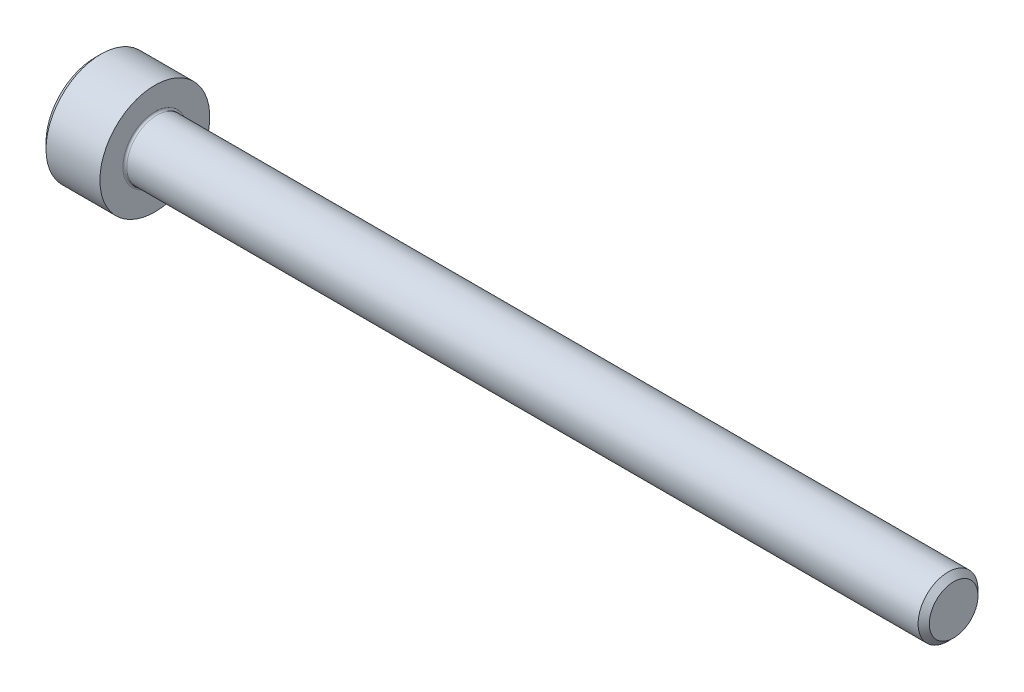
SolidWorks part; units mm, degrees
ref_plane "Plane1" through (0, 0, 0) normal (0, 0, 1) x (1, 0, 0)
ref_plane "Plane2" through (0, 0, 0) normal (0, 1, 0) x (1, 0, 0)
ref_plane "Plane3" through (0, 0, 0) normal (1, 0, 0) x (0, 0, -1)
sketch "BodySke" plane through (0, 0, 0) normal (0, 0, 1) x (1, 0, 0)
  line L0 (0, 0) -> (0, 2.45)
  line L1 (0.3, 2.75) -> (3, 2.75)
  line L2 (3, 2.75) -> (3, 1.5)
  line L3 (3, 1.5) -> (42.7195, 1.5)
  line L4 (43, 1.2195) -> (43, 0)
  line L5 (43, 0) -> (0, 0)
  line L6 (-31.75, 0) -> (127, 0) construction
  line L7 (0, 2.45) -> (0.3, 2.75)
  line L8 (43, 1.2195) -> (42.7195, 1.5)
  line L9 (0, -2.45) -> (0.3, -2.75) construction
  line L10 (43, -1.2195) -> (42.7195, -1.5) construction
  line L11 (3.5, 9.525) -> (3.5, 3.175) construction
  line L12 (25, 9.525) -> (25, 3.175) construction
  line L13 (-7, 9.525) -> (-7, 3.175) construction
  dimension "Diameter" = 3
  dimension "Head_ht" = 3
  dimension "Length" = 40
  dimension "Body_ch_ang" = 45
  dimension "Head_dia" = 5.5
  dimension "Head_ch_ang" = 45
  dimension "Minor_dia" = 2.439
  dimension "Advance" = 0.5
  dimension "Thread_nom" = 18
  dimension "Thread_length" = 50
  dimension "Head_ch_ht" = 0.3
revolve "Base-Revolve" add sketch "BodySke"
cosmetic thread "ThreadCosmetic" [suppressed]
fillet "Fillet1" radius 0.1 1 edges at (3, 0, 1.5)
sketch "Sketch2" plane through (0, 0, 0) normal (0, 0, 1) x (1, 0, 0)
  line L0 (0, 1.28) -> (1.3, 1.28)
  line L1 (1.3, 1.28) -> (2.039, 0)
  line L2 (-31.75, 0) -> (127, 0) construction
  line L3 (2.039, 0) -> (0, 0)
  line L4 (0, 0) -> (0, 1.28)
  line L5 (0, 2.45) -> (0, -2.45) construction
  line L6 (0, 0) -> (47.625, 0) construction
  line L7 (3, -2.75) -> (3, 2.75) construction
  dimension "D1" = 1.28
  dimension "D2" = 60
  dimension "Wall_thickness" = 1.7
revolve "Hex-PreBroach" cut sketch "Sketch2" angle 360 about L6
sketch "Sketch3" plane through (0, 0, 0) normal (-1, 0, 0) x (0, 0.5, 0.866)
  line L0 (0.739, 1.28) -> (-0.739, 1.28)
  line L1 (-0.739, 1.28) -> (-1.478, 0)
  line L2 (0.739, 1.28) -> (1.478, 0)
  line L3 (0.739, -1.28) -> (1.478, 0)
  line L4 (0.739, -1.28) -> (-0.739, -1.28)
  line L5 (-0.739, -1.28) -> (-1.478, 0)
  dimension "D1" = 1.28
  dimension "D2" = 1.28
  dimension "Hex_size" = 2.56
extrude "Hex" cut sketch "Sketch3" against normal blind 1.3
sketch "Sketch4" plane through (0, 0, 0) normal (-1, 0, 0) x (0, 0, 1)
  line L0 (0, 0) -> (1.4605, 0)
  line L1 (0, 0) -> (6.1484, 3.5498) construction
  line L2 (0, 0) -> (0.7302, 1.2648)
  line L3 (1.2009, 0.3267) -> (1.3933, 0.4378)
  line L4 (0.8834, 0.8767) -> (1.0758, 0.9877)
  arc A0 (1.2009, 0.3267) -> (0.8834, 0.8767) centre (0, 0) ccw
  arc A1 (1.4605, 0) -> (1.3933, 0.4378) centre (0, 0) ccw
  arc A2 (0.7302, 1.2648) -> (1.0758, 0.9877) centre (0, 0) cw
  dimension "D1" = 30
  dimension "Spline_n_dim" = 2.4892
  dimension "Spline_m_dim" = 2.921
  dimension "D2" = 60
  dimension "D3" = 0.3175
  dimension "Spline_p_dim" = 0.635
extrude "Spline" [suppressed] cut sketch "Sketch4" against normal blind 1.3
pattern_circular "CirPattern1" [suppressed] count 6 every 60
sketch "Sketch5" plane through (0, 0, 0) normal (0, 0, 1) x (1, 0, 0)
  line L0 (-31.75, 0) -> (127, 0) construction
  line L2 (0, 2.45) -> (0, -2.45) construction
  circle A0 centre (1.2, 0) radius 0.475
  dimension "Drilled_hole_dia" = 0.95
  dimension "Drilled_hole_loc" = 1.2
extrude "Hole" [suppressed] cut sketch "Sketch5" against normal through all and the other way through all
pattern_circular "Drilled-4" [suppressed] count 2 every 60
pattern_circular "Drilled-6" [suppressed] count 3 every 60
sketch "ThdSchSke" plane through (0, 0, 0) normal (0, 0, 1) x (1, 0, 0)
  line L0 (25, -1.2195) -> (24.8036, -1.5)
  line L1 (25, -1.2195) -> (25.1964, -1.5)
  line L2 (25.1964, -1.5) -> (25.1964, -1.875)
  line L3 (-3.175, 0) -> (5.1513, 0) construction
  line L5 (25.1964, -1.875) -> (24.8036, -1.875)
  line L6 (24.8036, -1.875) -> (24.8036, -1.5)
  line L7 (0, 2.45) -> (0, -2.45) construction
  dimension "Thread_minor" = 2.439
  dimension "Diameter" = 3
  dimension "Start" = 25
  dimension "SideAngle" = 55
  dimension "VeeAngle" = 70
  dimension "Overcut" = 3.75
revolve "ThreadSchematic" [suppressed] cut sketch "ThdSchSke" angle 360 about L3
pattern_linear "ThdSchPat" [suppressed]
equation "\"D2@Sketch3\" = \"Hex_size@Sketch3\" / 2"
equation "\"D1@Sketch3\" = \"Hex_size@Sketch3\" / 2"
equation "\"D1@Sketch2\" = \"Hex_size@Sketch3\" / 2"
equation "\"D3@Sketch4\" = \"Spline_p_dim@Sketch4\" / 2"
equation "\"Thread_minor@ThreadCosmetic\"  =  \"Minor_dia@BodySke\""
equation "\"D2@CirPattern1\" = 360 / \"Num_teeth@CirPattern1\""
equation "\"Wall_thickness@Sketch2\" = \"Head_ht@BodySke\" - \"Key_eng@Hex\""
equation "\"Thread_length@ThreadCosmetic\" = ((sgn( (\"Length@BodySke\" - \"Advance@BodySke\" ) - \"Thread_nom@BodySke\" )-1)*( (\"Length@BodySke\" - \"Advance@BodySke\" ) - \"Thread_nom@BodySke\" ))/-2+ \"Thread_nom@BodySke\""
equation "\"Thread_minor@ThdSchSke\" = \"Minor_dia@BodySke\""
equation "\"Diameter@ThdSchSke\" = \"Diameter@BodySke\""
equation "\"Overcut@ThdSchSke\" = \"Diameter@BodySke\" * 1.25"
equation "\"Start@ThdSchSke\" = \"Head_ht@BodySke\" + \"Length@BodySke\" - \"Thread_length@ThreadCosmetic\"  '---Non-countersunk---"
equation "\"Num_threads@ThdSchPat\" = int( \"Thread_length@ThreadCosmetic\" / \"Advance@BodySke\" + 0.999 )  + 1"
equation "\"Advance@ThdSchPat\" = \"Thread_length@ThreadCosmetic\" /  (\"Num_threads@ThdSchPat\" - 1) 'relax it"
equation "\"Num_threads@ThdSchPat\" = \"Num_threads@ThdSchPat\" - sgn( \"Num_threads@ThdSchPat\" - 1) '---chamfered tips only---"
